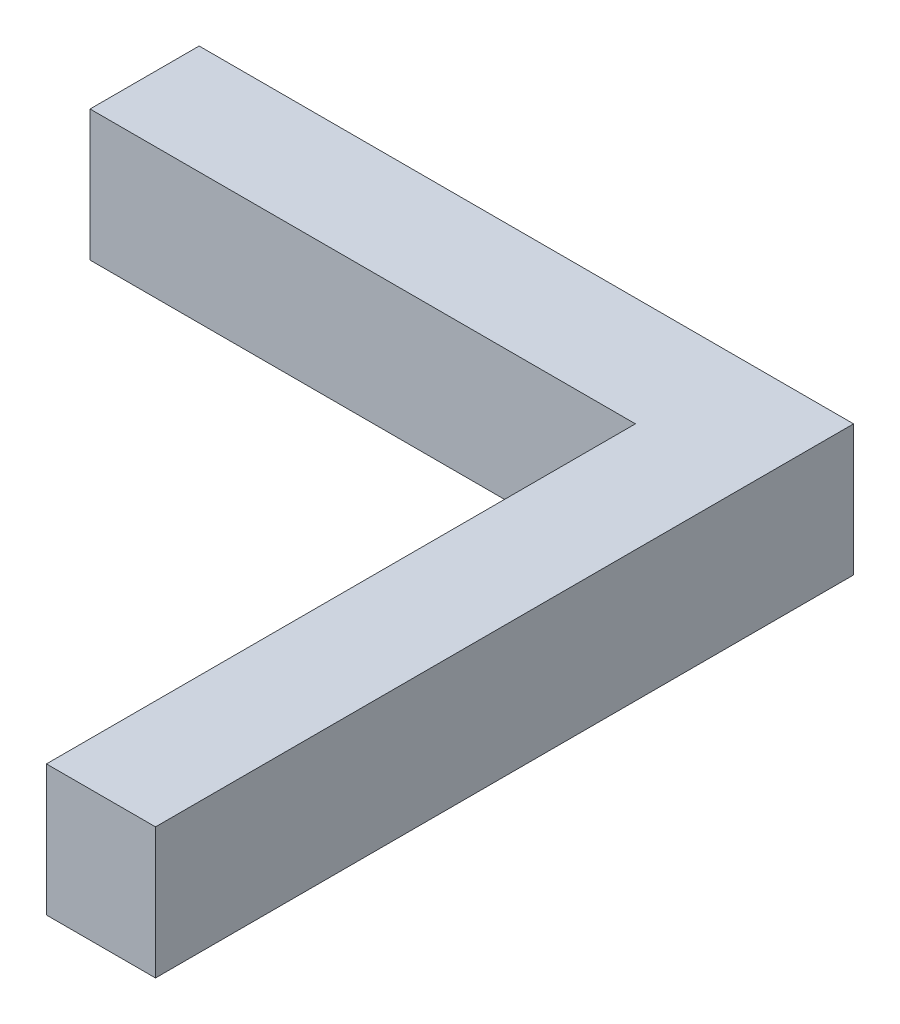
SolidWorks part; units mm, degrees
ref_plane "Ön Düzlem" through (0, 0, 0) normal (0, 0, 1) x (1, 0, 0)
ref_plane "Üst Düzlem" through (0, 0, 0) normal (0, 1, 0) x (1, 0, 0)
ref_plane "Sağ Düzlem" through (0, 0, 0) normal (1, 0, 0) x (0, 0, -1)
sketch "Sketch1" plane through (0, 0, 0) normal (0, 1, 0) x (1, 0, 0)
  line L0 (0, 0) -> (60, 0)
  line L1 (60, 0) -> (60, -64)
  line L2 (60, -64) -> (50, -64)
  line L3 (50, -64) -> (50, -10)
  line L4 (50, -10) -> (0, -10)
  line L5 (0, -10) -> (0, 0)
  dimension "D1" = 50
  dimension "D2" = 64
  dimension "D3" = 10
  dimension "D4" = 10
extrude "Boss-Extrude1" add sketch "Sketch1" along normal blind 12
